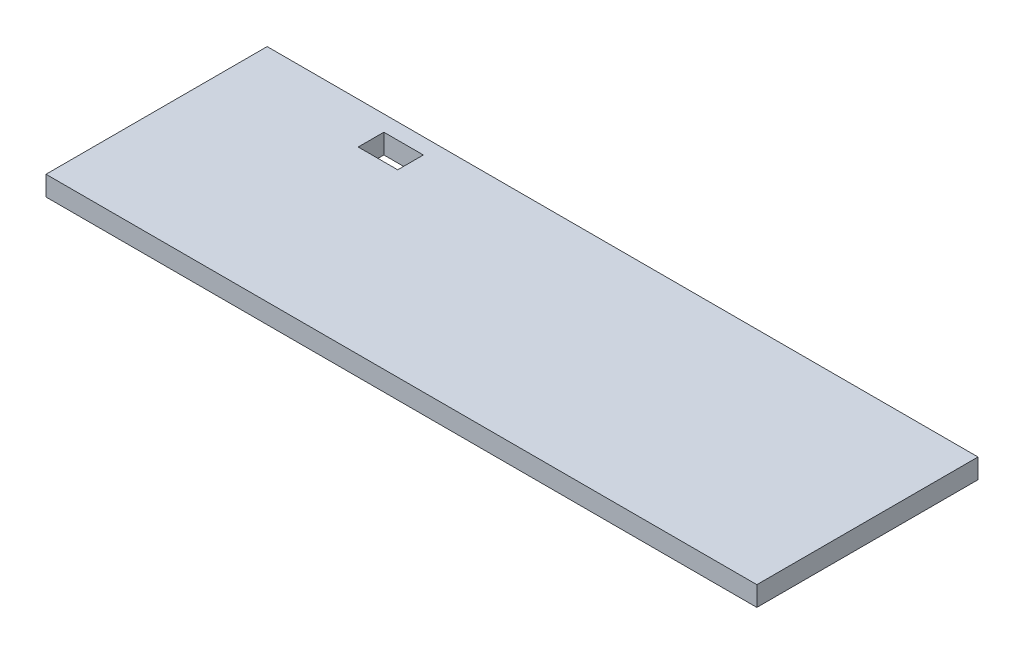
SolidWorks part; units mm, degrees
ref_plane "Ön Düzlem" through (0, 0, 0) normal (0, 0, 1) x (1, 0, 0)
ref_plane "Üst Düzlem" through (0, 0, 0) normal (0, 1, 0) x (1, 0, 0)
ref_plane "Sağ Düzlem" through (0, 0, 0) normal (1, 0, 0) x (0, 0, -1)
sketch "Çizim1" plane through (0, 0, 0) normal (0, 1, 0) x (1, 0, 0)
  line L1 (-90, -28) -> (90, -28)
  line L2 (-90, -28) -> (-90, 28)
  line L3 (-90, 28) -> (90, 28)
  line L4 (90, -28) -> (90, 28)
  line L5 (0, 28) -> (0, -28) construction
  line L6 (-90, 0) -> (90, 0) construction
  line L7 (-56.4434, 24) -> (-46.4434, 24)
  line L8 (-56.4434, 24) -> (-56.4434, 17.5)
  line L9 (-56.4434, 17.5) -> (-46.4434, 17.5)
  line L10 (-46.4434, 24) -> (-46.4434, 17.5)
  line L11 (-51.4434, 17.5) -> (-51.4434, 24) construction
  line L12 (-56.4434, 20.75) -> (-46.4434, 20.75) construction
  point P0 (0, 0)
  point P4 (-51.4434, 20.75)
  dimension "D1" = 180
  dimension "D2" = 56
  dimension "D3" = 10
  dimension "D4" = 6.5
  dimension "D5" = 4
extrude "Yükseklik-Ekstrüzyon1" add sketch "Çizim1" along normal blind 5
